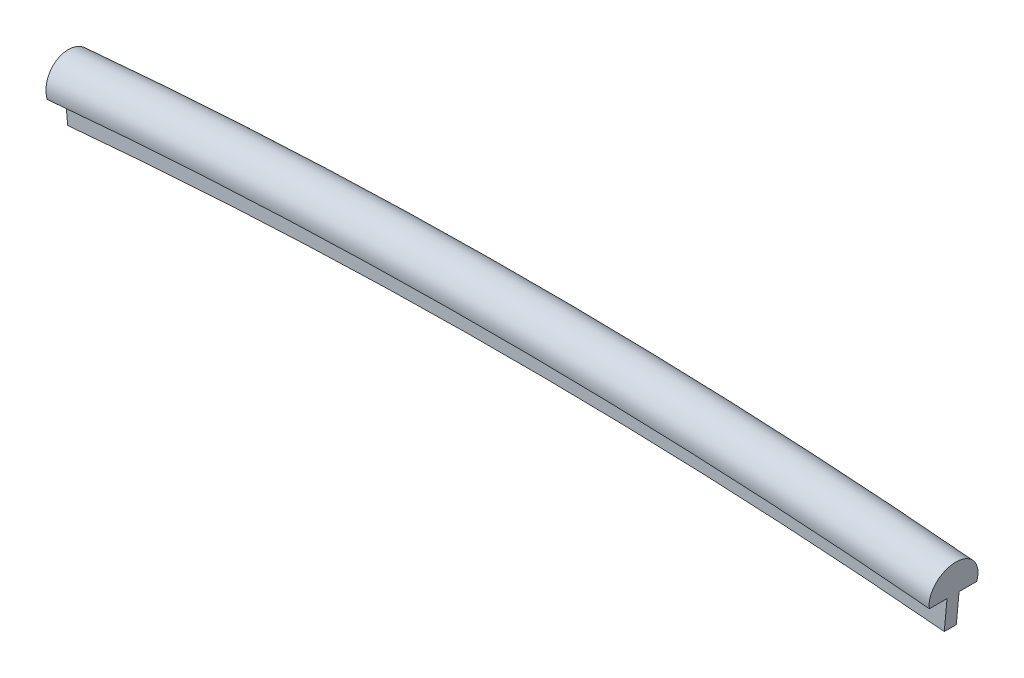
SolidWorks part; units mm, degrees
ref_plane "Front Plane" through (0, 0, 0) normal (0, 0, 1) x (1, 0, 0)
ref_plane "Top Plane" through (0, 0, 0) normal (0, 1, 0) x (1, 0, 0)
ref_plane "Right Plane" through (0, 0, 0) normal (1, 0, 0) x (0, 0, -1)
sketch "Sketch2" plane through (0, 0, 0) normal (1, 0, 0) x (0, 0, -1)
  line L0 (0, 241.3) -> (0, 0) construction
  line L2 (0, 241.3) -> (0, 239.8) construction
  line L3 (0, 239.8) -> (0.3, 239.8)
  line L4 (0, 239.8) -> (-0.3, 239.8)
  line L5 (-0.3, 239.8) -> (-0.3, 241.3)
  line L6 (0.3, 239.8) -> (0.3, 241.3)
  line L7 (0, 241.3) -> (0, 242.8) construction
  line L8 (-1.18, 241.3) -> (-0.3, 241.3)
  line L9 (0.3, 241.3) -> (1.18, 241.3)
  arc A0 (-1.18, 241.3) -> (1.18, 241.3) centre (0, 241.586) cw
  point P14 (0, 241.3)
ref_axis "Axis2" through (0, 0, 70.5976) along (0, 0, -1)
revolve "Revolve1" add sketch "Sketch2" angle 5.23 about axis through (0, 0, 70.5976) along (0, 0, -1)
